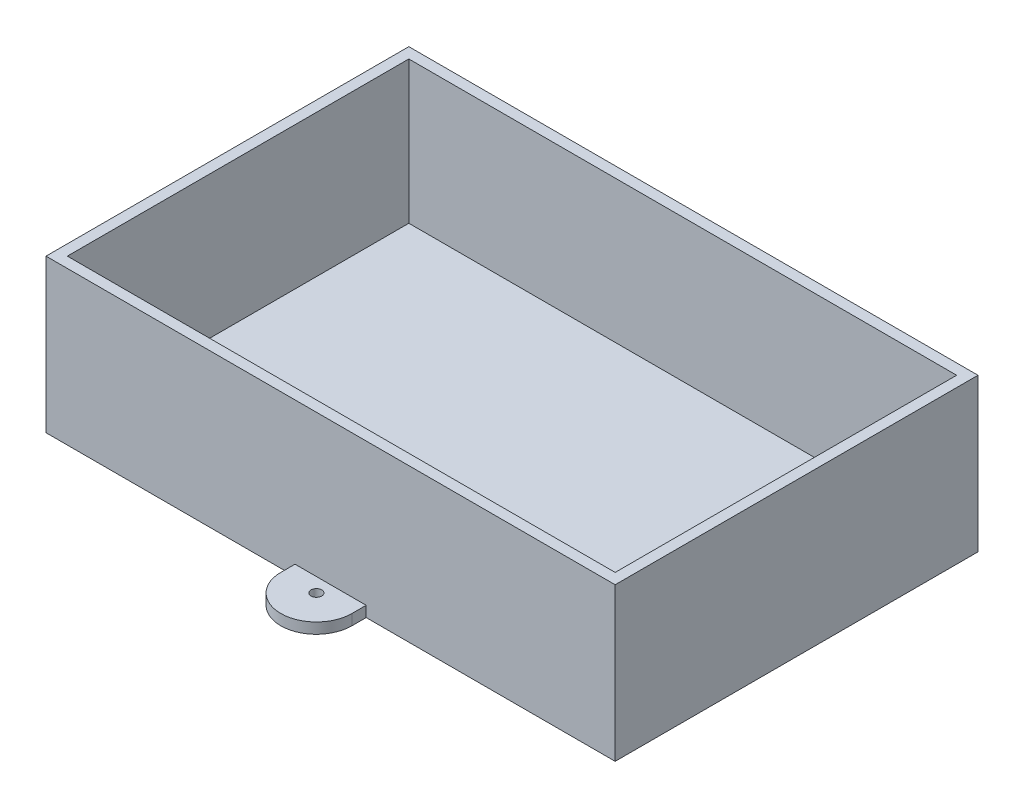
SolidWorks part; units mm, degrees
ref_plane "Front Plane" through (0, 0, 0) normal (0, 0, 1) x (1, 0, 0)
ref_plane "Top Plane" through (0, 0, 0) normal (0, 1, 0) x (1, 0, 0)
ref_plane "Right Plane" through (0, 0, 0) normal (1, 0, 0) x (0, 0, -1)
other "mount2"
sketch "Sketch1" plane through (0, 0, 0) normal (0, 1, 0) x (1, 0, 0)
  line L0 (-3, 3) -> (-3, -99)
  line L1 (0, 0) -> (154, 0)
  line L2 (0, 0) -> (0, -96)
  line L3 (0, -96) -> (154, -96)
  line L4 (154, 0) -> (154, -96)
  line L5 (-3, -99) -> (157, -99)
  line L6 (157, 3) -> (157, -99)
  line L7 (-3, 3) -> (157, 3)
  dimension "D1" = 154
  dimension "D2" = 96
  dimension "D3" = 3
extrude "Boss-Extrude1" add sketch "Sketch1" along normal blind 40
sketch "Sketch2" plane through (0, 0, 0) normal (0, -1, 0) x (1, 0, 0)
  line L1 (-3, 99) -> (157, 99)
  line L2 (-3, 99) -> (-3, -3)
  line L3 (-3, -3) -> (157, -3)
  line L4 (157, 99) -> (157, -3)
extrude "Boss-Extrude2" add sketch "Sketch2" along normal blind 3
sketch "Sketch3" plane through (0, -3, 0) normal (0, -1, 0) x (1, 0, 0)
  line L0 (77, 103) -> (77, -7) construction
  line L1 (87, 103) -> (87, -7)
  line L2 (67, 103) -> (67, -7)
  line L3 (157, -3) -> (157, 99) construction
  line L4 (-3, -3) -> (157, -3) construction
  line L8 (157, 99) -> (-3, 99) construction
  arc A0 (87, 103) -> (67, 103) centre (77, 103) ccw
  arc A1 (67, -7) -> (87, -7) centre (77, -7) ccw
  circle A2 centre (77, -7) radius 1.5
  circle A3 centre (77, 103) radius 1.5
  point P2 (77, 48)
  dimension "D1" = 10
  dimension "D5" = 3
  dimension "D6" = 3
  dimension "D2" = 4
  dimension "D3" = 80
  dimension "D4" = 4
extrude "Boss-Extrude3" add sketch "Sketch3" against normal blind 3 contours L2 A1 L1 A0 | A3 | A2
